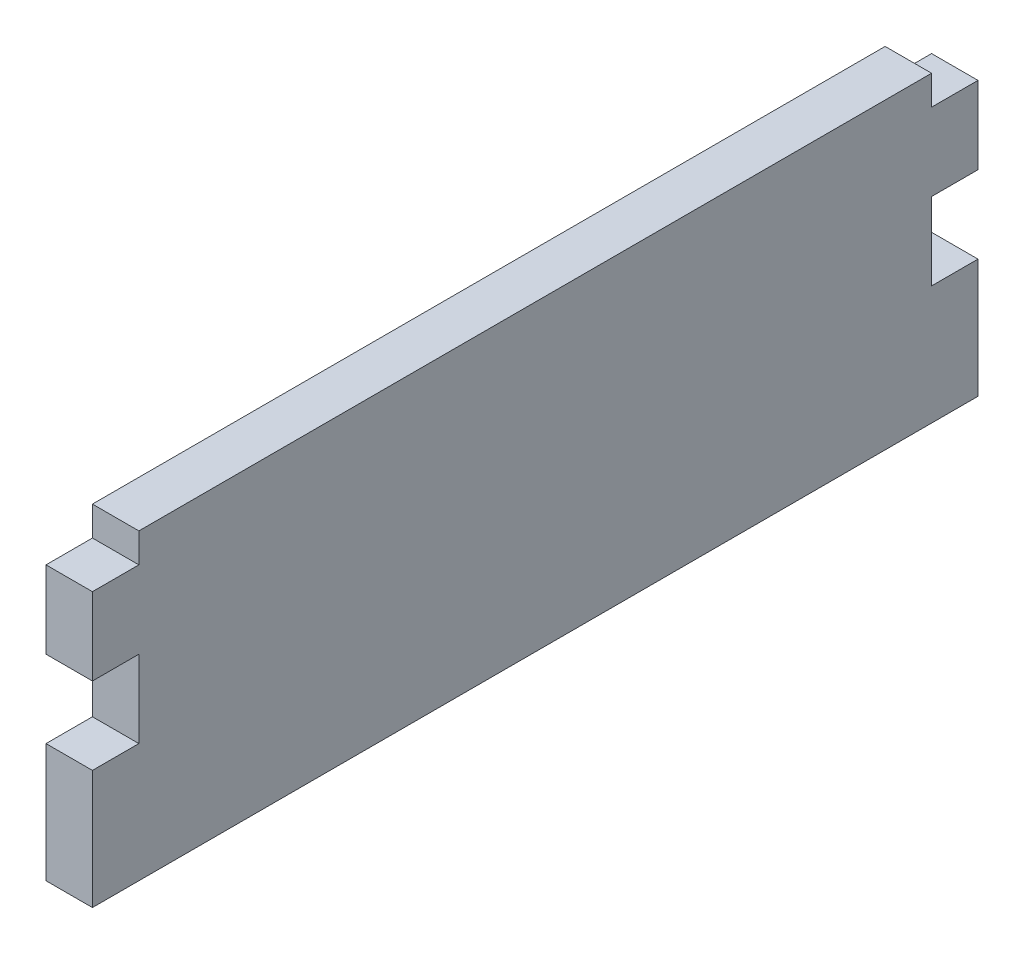
SolidWorks part; units mm, degrees
ref_plane "Спереди" through (0, 0, 0) normal (0, 0, 1) x (1, 0, 0)
ref_plane "Сверху" through (0, 0, 0) normal (0, 1, 0) x (1, 0, 0)
ref_plane "Справа" through (0, 0, 0) normal (1, 0, 0) x (0, 0, -1)
sketch "Эскиз1" plane through (0, 0, 0) normal (1, 0, 0) x (0, 0, -1)
  line L0 (-142.5825, -84.6816) -> (-136.5825, -84.6816) construction
  line L1 (-2.9825, -73.2482) -> (-105.4125, -73.2482) construction
  line L2 (7.7798, -91.3916) -> (7.7798, -95.3916) construction
  line L3 (3.0175, -135.7301) -> (3.0175, -136.7454)
  line L5 (3.0175, -136.7454) -> (-111.4125, -136.7454)
  line L6 (-105.4125, -101.3916) -> (-111.4125, -101.3916)
  line L7 (-105.4125, -101.3916) -> (-105.4125, -97.5916)
  line L8 (-105.4125, -97.5916) -> (-2.9825, -97.5916) construction
  line L9 (-105.4125, -97.5916) -> (-2.9825, -97.5916)
  line L10 (-2.9825, -97.5916) -> (-2.9825, -101.3916)
  line L11 (-111.4125, -136.7454) -> (-111.4125, -135.7301)
  line L14 (3.0175, -87.9576) -> (-2.9825, -87.9576) construction
  line L16 (-2.9825, -101.3916) -> (3.0175, -101.3916)
  line L17 (3.0175, -101.3916) -> (3.0175, -111.3916)
  line L18 (3.0175, -111.3916) -> (-2.9825, -111.3916)
  line L19 (-2.9825, -111.3916) -> (-2.9825, -121.3916)
  line L20 (-2.9825, -121.3916) -> (3.0175, -121.3916)
  line L21 (3.0175, -121.3916) -> (3.0175, -135.7301)
  line L22 (-111.4125, -101.3916) -> (-111.4125, -111.3916)
  line L23 (-111.4125, -111.3916) -> (-105.4125, -111.3916)
  line L24 (-105.4125, -111.3916) -> (-105.4125, -121.3916)
  line L25 (-105.4125, -121.3916) -> (-111.4125, -121.3916)
  line L26 (-111.4125, -121.3916) -> (-111.4125, -135.7301)
  point P0 (-69.7825, -114.2816)
  dimension "D1" = 6
  dimension "D2" = 102.43
  dimension "D3" = 6
  dimension "D4" = 6
  dimension "D5" = 3.8
  dimension "D7" = 10
  dimension "D8" = 4
extrude "Бобышка-Вытянуть1" add sketch "Эскиз1" along normal blind 6 contours L16 L17 L18 L19 L20 L21 L3 L5 L11 L26 L25 L24 L23 L22 L6 L7 L9 L10
